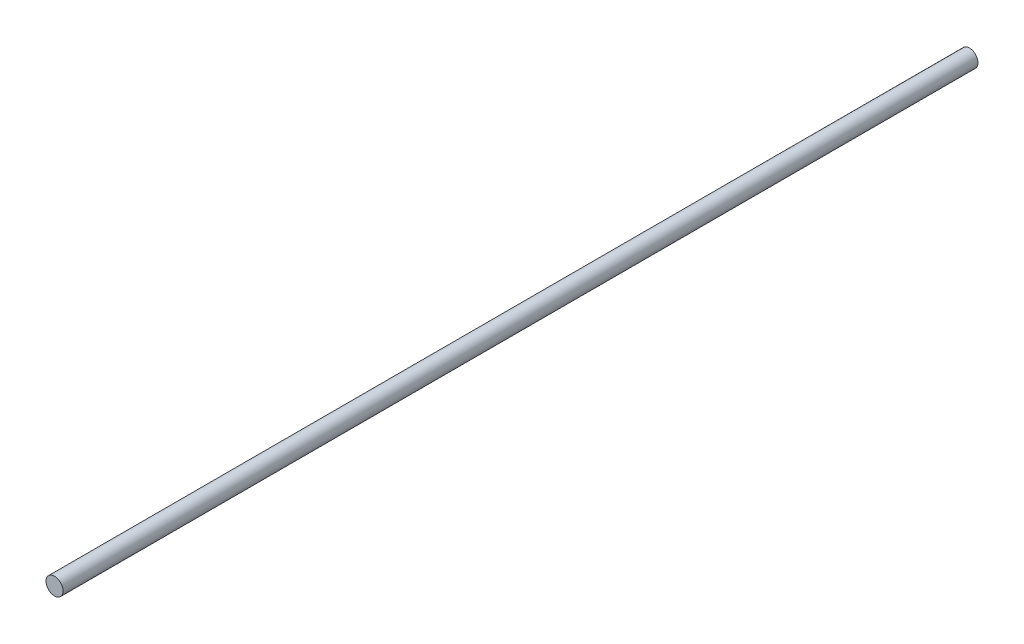
SolidWorks part; units mm, degrees
ref_plane "前视基准面" through (0, 0, 0) normal (0, 0, 1) x (1, 0, 0)
ref_plane "上视基准面" through (0, 0, 0) normal (0, 1, 0) x (1, 0, 0)
ref_plane "右视基准面" through (0, 0, 0) normal (1, 0, 0) x (0, 0, -1)
other "Configuration Table"
sketch "草图1" plane through (0, 0, 0) normal (0, 0, 1) x (1, 0, 0)
  circle A0 centre (0, 0) radius 2
  dimension "diameter" = 4
extrude "Cable_envelope" add sketch "草图1" along normal blind 214
